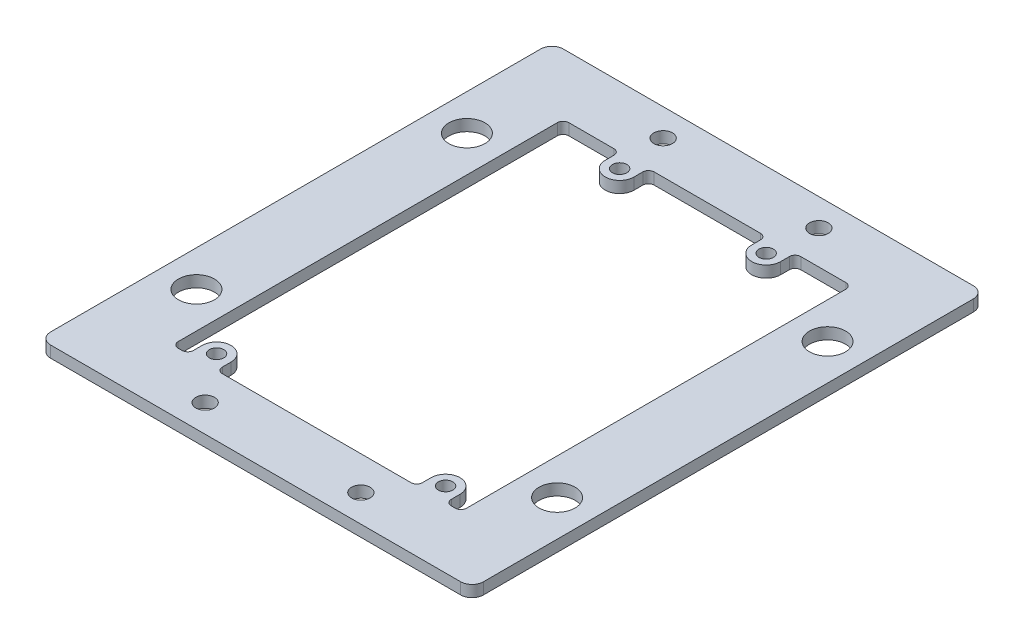
SolidWorks part; units mm, degrees
material "6061 Alloy"
ref_plane "Front Plane" through (0, 0, 0) normal (0, 0, 1) x (1, 0, 0)
ref_plane "Top Plane" through (0, 0, 0) normal (0, 1, 0) x (1, 0, 0)
ref_plane "Right Plane" through (0, 0, 0) normal (1, 0, 0) x (0, 0, -1)
sketch "Sketch1" plane through (0, 0, 0) normal (0, 1, 0) x (1, 0, 0)
  line L1 (-60, 71.08) -> (60, 71.08)
  line L2 (-60, 71.08) -> (-60, -71.08)
  line L3 (-60, -71.08) -> (60, -71.08)
  line L4 (60, 71.08) -> (60, -71.08)
  line L5 (-60, 71.08) -> (60, -71.08) construction
  line L6 (-60, -71.08) -> (60, 71.08) construction
  point P0 (0, 0)
  dimension "D1" = 142.16
  dimension "D2" = 120
extrude "Boss-Extrude1" add sketch "Sketch1" along normal blind 3.175
sketch "Sketch2" plane through (0, 3.175, 0) normal (0, 1, 0) x (1, 0, 0)
  line L1 (-50, 37.5) -> (50, 37.5) construction
  line L2 (-50, 37.5) -> (-50, -37.5) construction
  line L3 (-50, -37.5) -> (50, -37.5) construction
  line L4 (50, 37.5) -> (50, -37.5) construction
  line L5 (-50, 37.5) -> (50, -37.5) construction
  line L6 (-50, -37.5) -> (50, 37.5) construction
  circle A0 centre (-50, -37.5) radius 5
  circle A1 centre (50, -37.5) radius 5
  circle A2 centre (50, 37.5) radius 5
  circle A3 centre (-50, 37.5) radius 5
  point P0 (0, 0)
  dimension "D1" = 10
  dimension "D2" = 100
  dimension "D3" = 75
extrude "Cut-Extrude1" cut sketch "Sketch2" against normal through all
sketch "Sketch3" plane through (0, 3.175, 0) normal (0, 1, 0) x (1, 0, 0)
  line L0 (20.32, 50.165) -> (31.75, -50.165) construction
  line L1 (31.75, -50.165) -> (-31.75, -50.165) construction
  line L2 (-31.75, -50.165) -> (-20.32, 50.165) construction
  line L3 (-20.32, 50.165) -> (20.32, 50.165) construction
  line L4 (0, 50.165) -> (0, -50.165) construction
  line L5 (-16.32, 50.165) -> (-16.32, 54.165)
  line L7 (-16.32, 54.165) -> (16.32, 54.165)
  line L8 (16.32, 54.165) -> (16.32, 50.165)
  line L9 (24.32, 50.165) -> (24.32, 54.165)
  line L10 (24.32, 54.165) -> (40, 54.165)
  line L11 (40, 54.165) -> (40, -54.165)
  line L12 (40, -54.165) -> (35.75, -54.165)
  line L13 (35.75, -54.165) -> (35.75, -50.165)
  line L14 (27.75, -50.165) -> (27.75, -54.165)
  line L15 (27.75, -54.165) -> (-27.75, -54.165)
  line L16 (-27.75, -54.165) -> (-27.75, -50.165)
  line L17 (-35.75, -50.165) -> (-35.75, -54.165)
  line L18 (-35.75, -54.165) -> (-40, -54.165)
  line L19 (-40, -54.165) -> (-40, 54.165)
  line L20 (-40, 54.165) -> (-24.32, 54.165)
  line L21 (-24.32, 54.165) -> (-24.32, 50.165)
  circle A0 centre (31.75, -50.165) radius 2
  circle A1 centre (-31.75, -50.165) radius 2
  circle A2 centre (20.32, 50.165) radius 2
  circle A3 centre (-20.32, 50.165) radius 2
  arc A4 (-24.32, 50.165) -> (-16.32, 50.165) centre (-20.32, 50.165) ccw
  arc A5 (16.32, 50.165) -> (24.32, 50.165) centre (20.32, 50.165) ccw
  arc A6 (35.75, -50.165) -> (27.75, -50.165) centre (31.75, -50.165) ccw
  arc A7 (-27.75, -50.165) -> (-35.75, -50.165) centre (-31.75, -50.165) ccw
  circle A10 centre (50, 37.5) radius 5 construction
  point P14 (0, 0)
  point P19 (0, 0)
  point P31 (0, 0)
  point P36 (0, 0)
  point P40 (31.75, -46.2988)
  point P41 (0, 0)
  dimension "D4" = 4
  dimension "D5" = 2
  dimension "D6" = 2
  dimension "D7" = 80
  dimension "D9" = 2
  dimension "D10" = 2
  dimension "D1" = 63.5
  dimension "D2" = 40.64
  dimension "D3" = 100.979
  dimension "D8" = 10
  dimension "D11" = 4
  dimension "D12" = 4
extrude "Cut-Extrude2" cut sketch "Sketch3" against normal through all
sketch "Sketch4" plane through (0, 3.175, 0) normal (0, 1, 0) x (1, 0, 0)
  line L0 (0, 0) -> (0, 63.5) construction
  line L1 (-21.59, 63.5) -> (21.59, 63.5) construction
  line L2 (0, 0) -> (28.9683, 0) construction
  line L3 (-21.59, -63.5) -> (21.59, -63.5) construction
  circle A0 centre (-21.59, 63.5) radius 2.5797
  circle A1 centre (21.59, 63.5) radius 2.5797
  circle A2 centre (-21.59, -63.5) radius 2.5797
  circle A3 centre (21.59, -63.5) radius 2.5797
  point P8 (0, 63.5)
  dimension "D2" = 5.1594
  dimension "D3" = 127
  dimension "D1" = 43.18
extrude "Cut-Extrude3" cut sketch "Sketch4" against normal through all
fillet "Fillet1" radius 1.5875 12 edges at (40, 1.5875, -54.165) (24.32, 1.5875, -54.165) (16.32, 1.5875, -54.165) (-16.32, 1.5875, -54.165) (-24.32, 1.5875, -54.165) (-40, 1.5875, -54.165) (27.75, 1.5875, 54.165) (-27.75, 1.5875, 54.165) (-40, 1.5875, 54.165) (-35.75, 1.5875, 54.165) (40, 1.5875, 54.165) (35.75, 1.5875, 54.165)
fillet "Fillet2" radius 3.175 4 edges at (-60, 1.5875, -71.08) (60, 1.5875, -71.08) (60, 1.5875, 71.08) (-60, 1.5875, 71.08)
